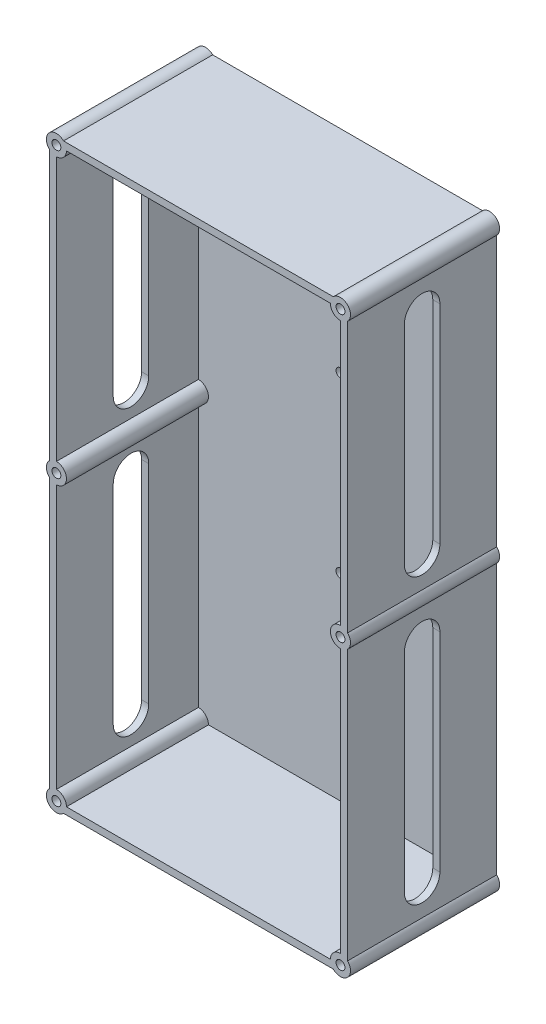
SolidWorks part; units mm, degrees
ref_plane "Front Plane" through (0, 0, 0) normal (0, 0, 1) x (1, 0, 0)
ref_plane "Top Plane" through (0, 0, 0) normal (0, 1, 0) x (1, 0, 0)
ref_plane "Right Plane" through (0, 0, 0) normal (1, 0, 0) x (0, 0, -1)
sketch "Sketch1" plane through (0, 0, 0) normal (0, 0, 1) x (1, 0, 0)
  line L1 (50.8, 101.6) -> (-50.8, 101.6)
  line L2 (50.8, 101.6) -> (50.8, -101.6)
  line L3 (50.8, -101.6) -> (-50.8, -101.6)
  line L4 (-50.8, 101.6) -> (-50.8, -101.6)
  line L5 (50.8, 101.6) -> (-50.8, -101.6) construction
  line L6 (50.8, -101.6) -> (-50.8, 101.6) construction
  point P0 (0, 0)
  dimension "D1" = 203.2
  dimension "D2" = 101.6
extrude "Boss-Extrude1" add sketch "Sketch1" along normal blind 50.8
shell "Shell1" thickness 2.54
sketch "Sketch2" plane through (0, 0, 0) normal (0, 0, 1) x (1, 0, 0)
  line L0 (0, 31.0185) -> (0, 0) construction
  line L1 (0, 0) -> (0, -31.0185) construction
  circle A0 centre (0, 31.0185) radius 1.5875
  circle A1 centre (0, -31.0185) radius 1.5875
  dimension "D1" = 3.175
extrude "Cut-Extrude1" cut sketch "Sketch2" against normal blind 50.8
sketch "Sketch3" plane through (0, 0, 50.8) normal (0, 0, 1) x (1, 0, 0)
  line L0 (-50.8, 101.6) -> (-50.8, -101.6) construction
  line L1 (50.8, -101.6) -> (50.8, 101.6) construction
  line L2 (54.3921, 101.6) -> (54.3921, -101.6) construction
  circle A0 centre (-50.8, 101.6) radius 3.5921
  circle A1 centre (50.8, 101.6) radius 3.5921
  circle A2 centre (50.8, -101.6) radius 3.5921
  circle A3 centre (-50.8, -101.6) radius 3.5921
  circle A4 centre (-50.8, 0) radius 3.5921
  circle A5 centre (50.8, 0) radius 3.5921
extrude "Boss-Extrude2" add sketch "Sketch3" against normal up to surface (53.34 mm away) up to face at (-1.5875, 31.0185, -2.54)
sketch "Sketch4" plane through (0, 0, 50.8) normal (0, 0, 1) x (1, 0, 0)
  circle A0 centre (-50.8, 0) radius 1.5875
  circle A1 centre (50.8, 0) radius 1.5875
  circle A2 centre (50.8, 101.6) radius 1.5875
  circle A3 centre (-50.8, 101.6) radius 1.5875
  circle A4 centre (50.8, -101.6) radius 1.5875
  circle A5 centre (-50.8, -101.6) radius 1.5875
  dimension "D1" = 3.175
extrude "Cut-Extrude2" cut sketch "Sketch4" against normal through all
sketch "Sketch5" plane through (53.34, 0, 0) normal (1, 0, 0) x (0, 0, -1)
  line L0 (-24.13, 88.0136) -> (-24.13, 13.5864) construction
  line L1 (-17.78, 88.0136) -> (-17.78, 13.5864)
  line L2 (-30.48, 88.0136) -> (-30.48, 13.5864)
  line L3 (-50.8, 50.8) -> (2.54, 50.8) construction
  line L4 (2.54, 2.54) -> (-50.8, 2.54) construction
  line L5 (2.54, 2.54) -> (2.54, 99.06) construction
  line L6 (2.54, 99.06) -> (-50.8, 99.06) construction
  line L7 (-50.8, 2.54) -> (-50.8, 99.06) construction
  arc A0 (-17.78, 88.0136) -> (-30.48, 88.0136) centre (-24.13, 88.0136) ccw
  arc A1 (-30.48, 13.5864) -> (-17.78, 13.5864) centre (-24.13, 13.5864) ccw
  point P2 (-24.13, 50.8)
  point P15 (-24.7236, 50.8)
  point P16 (-24.13, 50.8)
  dimension "D1" = 12.7
extrude "Cut-Extrude3" cut sketch "Sketch5" against normal through all
mirror "Mirror1" about plane through (0, 0, 0) normal (0, 1, 0) of "Cut-Extrude3"
